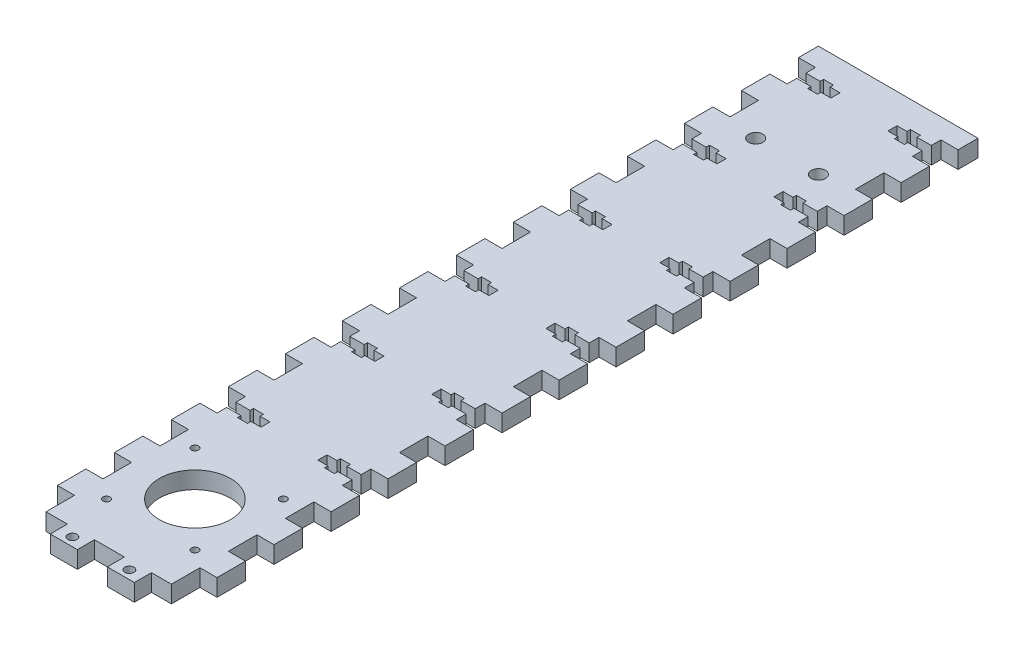
SolidWorks part; units mm, degrees
ref_plane "Plan de face" through (0, 0, 0) normal (0, 0, 1) x (1, 0, 0)
ref_plane "Plan de dessus" through (0, 0, 0) normal (0, 1, 0) x (1, 0, 0)
ref_plane "Plan de droite" through (0, 0, 0) normal (1, 0, 0) x (0, 0, -1)
sketch "Sketch1" plane through (0, 0, 0) normal (0, 0, 1) x (1, 0, 0)
  line L1 (-85.7436, 30.1282) -> (-29.7436, 30.1282)
  line L2 (-85.7436, 30.1282) -> (-85.7436, 24.1282)
  line L3 (-85.7436, 24.1282) -> (-29.7436, 24.1282)
  line L4 (-29.7436, 30.1282) -> (-29.7436, 24.1282)
  dimension "D1" = 56
  dimension "D2" = 6
extrude "Boss-Extrude1" add sketch "Sketch1" along normal blind 277
sketch "Sketch3" plane through (0, 30.1282, 0) normal (0, 1, 0) x (1, 0, 0)
  line L0 (-85.7436, -277) -> (-79.7436, -277)
  line L1 (-29.7436, -277) -> (-85.7436, -277) construction
  line L2 (-29.7436, 0) -> (-85.7436, 0) construction
  line L3 (-57.7436, 0) -> (-57.7436, -277) construction
  line L4 (-29.7436, -277) -> (-35.7436, -277)
  line L5 (-29.7436, -277) -> (-29.7436, -267)
  line L6 (-29.7436, -267) -> (-35.7436, -267)
  line L7 (-35.7436, -277) -> (-35.7436, -267)
  line L8 (-85.7436, -277) -> (-85.7436, -267)
  line L9 (-85.7436, -267) -> (-79.7436, -267)
  line L10 (-79.7436, -277) -> (-79.7436, -267)
  line L11 (-85.7436, -257) -> (-79.7436, -257)
  line L12 (-79.7436, -257) -> (-79.7436, -247)
  line L13 (-85.7436, -247) -> (-79.7436, -247)
  line L14 (-85.7436, -257) -> (-85.7436, -247)
  line L15 (-29.7436, -257) -> (-29.7436, -247)
  line L16 (-29.7436, -257) -> (-35.7436, -257)
  line L17 (-35.7436, -257) -> (-35.7436, -247)
  line L18 (-29.7436, -247) -> (-35.7436, -247)
  line L19 (-85.7436, -237) -> (-79.7436, -237)
  line L20 (-79.7436, -237) -> (-79.7436, -227)
  line L21 (-85.7436, -227) -> (-79.7436, -227)
  line L22 (-85.7436, -237) -> (-85.7436, -227)
  line L23 (-29.7436, -237) -> (-29.7436, -227)
  line L24 (-29.7436, -237) -> (-35.7436, -237)
  line L25 (-35.7436, -237) -> (-35.7436, -227)
  line L26 (-29.7436, -227) -> (-35.7436, -227)
  line L27 (-85.7436, -217) -> (-79.7436, -217)
  line L28 (-79.7436, -217) -> (-79.7436, -207)
  line L29 (-85.7436, -207) -> (-79.7436, -207)
  line L30 (-85.7436, -217) -> (-85.7436, -207)
  line L31 (-29.7436, -217) -> (-29.7436, -207)
  line L32 (-29.7436, -217) -> (-35.7436, -217)
  line L33 (-35.7436, -217) -> (-35.7436, -207)
  line L34 (-29.7436, -207) -> (-35.7436, -207)
  line L35 (-85.7436, -197) -> (-79.7436, -197)
  line L36 (-79.7436, -197) -> (-79.7436, -187)
  line L37 (-85.7436, -187) -> (-79.7436, -187)
  line L38 (-85.7436, -197) -> (-85.7436, -187)
  line L39 (-29.7436, -197) -> (-29.7436, -187)
  line L40 (-29.7436, -197) -> (-35.7436, -197)
  line L41 (-35.7436, -197) -> (-35.7436, -187)
  line L42 (-29.7436, -187) -> (-35.7436, -187)
  line L43 (-85.7436, -177) -> (-79.7436, -177)
  line L44 (-79.7436, -177) -> (-79.7436, -167)
  line L45 (-85.7436, -167) -> (-79.7436, -167)
  line L46 (-85.7436, -177) -> (-85.7436, -167)
  line L47 (-29.7436, -177) -> (-29.7436, -167)
  line L48 (-29.7436, -177) -> (-35.7436, -177)
  line L49 (-35.7436, -177) -> (-35.7436, -167)
  line L50 (-29.7436, -167) -> (-35.7436, -167)
  line L51 (-85.7436, -157) -> (-79.7436, -157)
  line L52 (-79.7436, -157) -> (-79.7436, -147)
  line L53 (-85.7436, -147) -> (-79.7436, -147)
  line L54 (-85.7436, -157) -> (-85.7436, -147)
  line L55 (-29.7436, -157) -> (-29.7436, -147)
  line L56 (-29.7436, -157) -> (-35.7436, -157)
  line L57 (-35.7436, -157) -> (-35.7436, -147)
  line L58 (-29.7436, -147) -> (-35.7436, -147)
  line L59 (-85.7436, -137) -> (-79.7436, -137)
  line L60 (-79.7436, -137) -> (-79.7436, -127)
  line L61 (-85.7436, -127) -> (-79.7436, -127)
  line L62 (-85.7436, -137) -> (-85.7436, -127)
  line L63 (-29.7436, -137) -> (-29.7436, -127)
  line L64 (-29.7436, -137) -> (-35.7436, -137)
  line L65 (-35.7436, -137) -> (-35.7436, -127)
  line L66 (-29.7436, -127) -> (-35.7436, -127)
  line L67 (-85.7436, -117) -> (-79.7436, -117)
  line L68 (-79.7436, -117) -> (-79.7436, -107)
  line L69 (-85.7436, -107) -> (-79.7436, -107)
  line L70 (-85.7436, -117) -> (-85.7436, -107)
  line L71 (-29.7436, -117) -> (-29.7436, -107)
  line L72 (-29.7436, -117) -> (-35.7436, -117)
  line L73 (-35.7436, -117) -> (-35.7436, -107)
  line L74 (-29.7436, -107) -> (-35.7436, -107)
  line L75 (-85.7436, -97) -> (-79.7436, -97)
  line L76 (-79.7436, -97) -> (-79.7436, -87)
  line L77 (-85.7436, -87) -> (-79.7436, -87)
  line L78 (-85.7436, -97) -> (-85.7436, -87)
  line L79 (-29.7436, -97) -> (-29.7436, -87)
  line L80 (-29.7436, -97) -> (-35.7436, -97)
  line L81 (-35.7436, -97) -> (-35.7436, -87)
  line L82 (-29.7436, -87) -> (-35.7436, -87)
  line L83 (-85.7436, -77) -> (-79.7436, -77)
  line L84 (-79.7436, -77) -> (-79.7436, -67)
  line L85 (-85.7436, -67) -> (-79.7436, -67)
  line L86 (-85.7436, -77) -> (-85.7436, -67)
  line L87 (-29.7436, -77) -> (-29.7436, -67)
  line L88 (-29.7436, -77) -> (-35.7436, -77)
  line L89 (-35.7436, -77) -> (-35.7436, -67)
  line L90 (-29.7436, -67) -> (-35.7436, -67)
  line L91 (-85.7436, -57) -> (-79.7436, -57)
  line L92 (-79.7436, -57) -> (-79.7436, -47)
  line L93 (-85.7436, -47) -> (-79.7436, -47)
  line L94 (-85.7436, -57) -> (-85.7436, -47)
  line L95 (-29.7436, -57) -> (-29.7436, -47)
  line L96 (-29.7436, -57) -> (-35.7436, -57)
  line L97 (-35.7436, -57) -> (-35.7436, -47)
  line L98 (-29.7436, -47) -> (-35.7436, -47)
  line L99 (-85.7436, -37) -> (-79.7436, -37)
  line L100 (-79.7436, -37) -> (-79.7436, -27)
  line L101 (-85.7436, -27) -> (-79.7436, -27)
  line L102 (-85.7436, -37) -> (-85.7436, -27)
  line L103 (-29.7436, -37) -> (-29.7436, -27)
  line L104 (-29.7436, -37) -> (-35.7436, -37)
  line L105 (-35.7436, -37) -> (-35.7436, -27)
  line L106 (-29.7436, -27) -> (-35.7436, -27)
  line L107 (-85.7436, -17) -> (-79.7436, -17)
  line L108 (-79.7436, -17) -> (-79.7436, -7)
  line L109 (-85.7436, -7) -> (-79.7436, -7)
  line L110 (-85.7436, -17) -> (-85.7436, -7)
  line L111 (-29.7436, -17) -> (-29.7436, -7)
  line L112 (-29.7436, -17) -> (-35.7436, -17)
  line L113 (-35.7436, -17) -> (-35.7436, -7)
  line L114 (-29.7436, -7) -> (-35.7436, -7)
  dimension "D1" = 6
  dimension "D2" = 10
  dimension "D3" = 14
extrude "Cut-Extrude1" cut sketch "Sketch3" against normal through all
sketch "Sketch6" plane through (0, 0, 277) normal (0, 0, 1) x (1, 0, 0)
  line L0 (-35.7436, 30.1282) -> (-79.7436, 30.1282) construction
  line L1 (-72.2436, 30.1282) -> (-62.7436, 30.1282)
  line L2 (-72.2436, 30.1282) -> (-72.2436, 24.1282)
  line L3 (-72.2436, 24.1282) -> (-62.7436, 24.1282)
  line L4 (-62.7436, 30.1282) -> (-62.7436, 24.1282)
  line L5 (-79.7436, 24.1282) -> (-35.7436, 24.1282) construction
  line L6 (-79.7436, 24.1282) -> (-79.7436, 30.1282) construction
  line L7 (-52.2436, 30.1282) -> (-52.2436, 24.1282)
  line L8 (-52.2436, 30.1282) -> (-42.7436, 30.1282)
  line L9 (-42.7436, 30.1282) -> (-42.7436, 24.1282)
  line L10 (-52.2436, 24.1282) -> (-42.7436, 24.1282)
  dimension "D1" = 7.5
  dimension "D2" = 9.5
  dimension "D3" = 2
extrude "Boss-Extrude2" add sketch "Sketch6" along normal blind 6
sketch "Sketch9" plane through (-35.7436, 0, 0) normal (1, 0, 0) x (0, 0, -1)
  line L0 (-257, 24.1282) -> (-247, 30.1282) construction
  line L1 (-247, 24.1282) -> (-257, 24.1282) construction
  line L2 (-250.4, 30.1282) -> (-253.6, 30.1282)
  line L3 (-250.4, 30.1282) -> (-250.4, 24.1282)
  line L4 (-250.4, 24.1282) -> (-253.6, 24.1282)
  line L5 (-253.6, 30.1282) -> (-253.6, 24.1282)
  line L6 (-250.4, 30.1282) -> (-253.6, 24.1282) construction
  line L7 (-250.4, 24.1282) -> (-253.6, 30.1282) construction
  line L8 (-210.4, 30.1282) -> (-210.4, 24.1282)
  line L9 (-210.4, 30.1282) -> (-213.6, 30.1282)
  line L10 (-213.6, 30.1282) -> (-213.6, 24.1282)
  line L11 (-210.4, 24.1282) -> (-213.6, 24.1282)
  line L12 (-170.4, 30.1282) -> (-170.4, 24.1282)
  line L13 (-170.4, 30.1282) -> (-173.6, 30.1282)
  line L14 (-173.6, 30.1282) -> (-173.6, 24.1282)
  line L15 (-170.4, 24.1282) -> (-173.6, 24.1282)
  line L16 (-130.4, 30.1282) -> (-130.4, 24.1282)
  line L17 (-130.4, 30.1282) -> (-133.6, 30.1282)
  line L18 (-133.6, 30.1282) -> (-133.6, 24.1282)
  line L19 (-130.4, 24.1282) -> (-133.6, 24.1282)
  line L20 (-90.4, 30.1282) -> (-90.4, 24.1282)
  line L21 (-90.4, 30.1282) -> (-93.6, 30.1282)
  line L22 (-93.6, 30.1282) -> (-93.6, 24.1282)
  line L23 (-90.4, 24.1282) -> (-93.6, 24.1282)
  line L24 (-50.4, 30.1282) -> (-50.4, 24.1282)
  line L25 (-50.4, 30.1282) -> (-53.6, 30.1282)
  line L26 (-53.6, 30.1282) -> (-53.6, 24.1282)
  line L27 (-50.4, 24.1282) -> (-53.6, 24.1282)
  line L28 (-10.4, 30.1282) -> (-10.4, 24.1282)
  line L29 (-10.4, 30.1282) -> (-13.6, 30.1282)
  line L30 (-13.6, 30.1282) -> (-13.6, 24.1282)
  line L31 (-10.4, 24.1282) -> (-13.6, 24.1282)
  point P4 (-252, 27.1282)
  dimension "D1" = 3.2
  dimension "D2" = 7
extrude "Cut-Extrude2" cut sketch "Sketch9" against normal blind 12
sketch "Sketch10" plane through (-79.7436, 0, 0) normal (-1, 0, 0) x (0, 0, 1)
  line L0 (257, 30.1282) -> (247, 24.1282) construction
  line L1 (257, 30.1282) -> (247, 30.1282) construction
  line L2 (250.4, 24.1282) -> (253.6, 24.1282)
  line L3 (250.4, 24.1282) -> (250.4, 30.1282)
  line L4 (250.4, 30.1282) -> (253.6, 30.1282)
  line L5 (253.6, 24.1282) -> (253.6, 30.1282)
  line L6 (250.4, 24.1282) -> (253.6, 30.1282) construction
  line L7 (250.4, 30.1282) -> (253.6, 24.1282) construction
  line L8 (210.4, 24.1282) -> (210.4, 30.1282)
  line L9 (210.4, 24.1282) -> (213.6, 24.1282)
  line L10 (213.6, 24.1282) -> (213.6, 30.1282)
  line L11 (210.4, 30.1282) -> (213.6, 30.1282)
  line L12 (170.4, 24.1282) -> (170.4, 30.1282)
  line L13 (170.4, 24.1282) -> (173.6, 24.1282)
  line L14 (173.6, 24.1282) -> (173.6, 30.1282)
  line L15 (170.4, 30.1282) -> (173.6, 30.1282)
  line L16 (130.4, 24.1282) -> (130.4, 30.1282)
  line L17 (130.4, 24.1282) -> (133.6, 24.1282)
  line L18 (133.6, 24.1282) -> (133.6, 30.1282)
  line L19 (130.4, 30.1282) -> (133.6, 30.1282)
  line L20 (90.4, 24.1282) -> (90.4, 30.1282)
  line L21 (90.4, 24.1282) -> (93.6, 24.1282)
  line L22 (93.6, 24.1282) -> (93.6, 30.1282)
  line L23 (90.4, 30.1282) -> (93.6, 30.1282)
  line L24 (50.4, 24.1282) -> (50.4, 30.1282)
  line L25 (50.4, 24.1282) -> (53.6, 24.1282)
  line L26 (53.6, 24.1282) -> (53.6, 30.1282)
  line L27 (50.4, 30.1282) -> (53.6, 30.1282)
  line L28 (10.4, 24.1282) -> (10.4, 30.1282)
  line L29 (10.4, 24.1282) -> (13.6, 24.1282)
  line L30 (13.6, 24.1282) -> (13.6, 30.1282)
  line L31 (10.4, 30.1282) -> (13.6, 30.1282)
  point P4 (252, 27.1282)
  dimension "D1" = 3.2
  dimension "D2" = 7
extrude "Cut-Extrude3" cut sketch "Sketch10" against normal blind 12
sketch "Sketch11" plane through (0, 24.1282, 0) normal (0, -1, 0) x (1, 0, 0)
  line L0 (-57.7436, 277) -> (-57.7436, 0) construction
  line L1 (-74.7436, 254.8) -> (-71.2436, 254.8)
  line L2 (-74.7436, 254.8) -> (-74.7436, 249.2)
  line L3 (-74.7436, 249.2) -> (-71.2436, 249.2)
  line L4 (-71.2436, 254.8) -> (-71.2436, 249.2)
  line L6 (-85.7436, 0) -> (-29.7436, 0) construction
  line L7 (-47.7436, 250.4) -> (-47.7436, 253.6) construction
  line L8 (-79.7436, 257) -> (-79.7436, 253.6) construction
  line L9 (-40.7436, 249.2) -> (-44.2436, 249.2)
  line L10 (-44.2436, 254.8) -> (-44.2436, 249.2)
  line L11 (-40.7436, 254.8) -> (-44.2436, 254.8)
  line L12 (-40.7436, 254.8) -> (-40.7436, 249.2)
  line L13 (-74.7436, 214.8) -> (-74.7436, 209.2)
  line L14 (-74.7436, 214.8) -> (-71.2436, 214.8)
  line L15 (-71.2436, 214.8) -> (-71.2436, 209.2)
  line L16 (-74.7436, 209.2) -> (-71.2436, 209.2)
  line L17 (-40.7436, 209.2) -> (-44.2436, 209.2)
  line L18 (-44.2436, 214.8) -> (-44.2436, 209.2)
  line L19 (-40.7436, 214.8) -> (-44.2436, 214.8)
  line L20 (-40.7436, 214.8) -> (-40.7436, 209.2)
  line L21 (-74.7436, 174.8) -> (-74.7436, 169.2)
  line L22 (-74.7436, 174.8) -> (-71.2436, 174.8)
  line L23 (-71.2436, 174.8) -> (-71.2436, 169.2)
  line L24 (-74.7436, 169.2) -> (-71.2436, 169.2)
  line L25 (-40.7436, 169.2) -> (-44.2436, 169.2)
  line L26 (-44.2436, 174.8) -> (-44.2436, 169.2)
  line L27 (-40.7436, 174.8) -> (-44.2436, 174.8)
  line L28 (-40.7436, 174.8) -> (-40.7436, 169.2)
  line L29 (-74.7436, 134.8) -> (-74.7436, 129.2)
  line L30 (-74.7436, 134.8) -> (-71.2436, 134.8)
  line L31 (-71.2436, 134.8) -> (-71.2436, 129.2)
  line L32 (-74.7436, 129.2) -> (-71.2436, 129.2)
  line L33 (-40.7436, 129.2) -> (-44.2436, 129.2)
  line L34 (-44.2436, 134.8) -> (-44.2436, 129.2)
  line L35 (-40.7436, 134.8) -> (-44.2436, 134.8)
  line L36 (-40.7436, 134.8) -> (-40.7436, 129.2)
  line L37 (-74.7436, 94.8) -> (-74.7436, 89.2)
  line L38 (-74.7436, 94.8) -> (-71.2436, 94.8)
  line L39 (-71.2436, 94.8) -> (-71.2436, 89.2)
  line L40 (-74.7436, 89.2) -> (-71.2436, 89.2)
  line L41 (-40.7436, 89.2) -> (-44.2436, 89.2)
  line L42 (-44.2436, 94.8) -> (-44.2436, 89.2)
  line L43 (-40.7436, 94.8) -> (-44.2436, 94.8)
  line L44 (-40.7436, 94.8) -> (-40.7436, 89.2)
  line L45 (-74.7436, 54.8) -> (-74.7436, 49.2)
  line L46 (-74.7436, 54.8) -> (-71.2436, 54.8)
  line L47 (-71.2436, 54.8) -> (-71.2436, 49.2)
  line L48 (-74.7436, 49.2) -> (-71.2436, 49.2)
  line L49 (-40.7436, 49.2) -> (-44.2436, 49.2)
  line L50 (-44.2436, 54.8) -> (-44.2436, 49.2)
  line L51 (-40.7436, 54.8) -> (-44.2436, 54.8)
  line L52 (-40.7436, 54.8) -> (-40.7436, 49.2)
  line L53 (-74.7436, 14.8) -> (-74.7436, 9.2)
  line L55 (-74.7436, 14.8) -> (-71.2436, 14.8)
  line L56 (-71.2436, 14.8) -> (-71.2436, 9.2)
  line L57 (-74.7436, 9.2) -> (-71.2436, 9.2)
  line L58 (-40.7436, 9.2) -> (-44.2436, 9.2)
  line L59 (-44.2436, 14.8) -> (-44.2436, 9.2)
  line L60 (-40.7436, 14.8) -> (-44.2436, 14.8)
  line L61 (-40.7436, 14.8) -> (-40.7436, 9.2)
  point P10 (-74.7436, 252)
  point P52 (-47.7436, 252)
  dimension "D1" = 5.6
  dimension "D3" = 5
  dimension "D4" = 3.5
  dimension "D5" = 7
extrude "Cut-Extrude4" cut sketch "Sketch11" against normal blind 12
sketch "Sketch12" plane through (0, 24.1282, 0) normal (0, -1, 0) x (1, 0, 0)
  line L2 (-52.2436, 283) -> (-52.2436, 277) construction
  line L3 (-42.7436, 283) -> (-52.2436, 283) construction
  line L4 (-62.7436, 283) -> (-72.2436, 283) construction
  circle A0 centre (-67.4936, 280) radius 1.6
  circle A1 centre (-47.4936, 280) radius 1.6
  point P2 (-52.2436, 280)
  point P5 (-47.4936, 283)
  point P12 (-67.4936, 283)
  dimension "D1" = 3.2
  dimension "D2" = 3.2
extrude "Cut-Extrude5" cut sketch "Sketch12" against normal blind 12
sketch "Sketch17" plane through (0, 30.1282, 0) normal (0, 1, 0) x (1, 0, 0)
  line L1 (-35.7436, -257) -> (-79.7436, -257)
  line L2 (-35.7436, -257) -> (-35.7436, -247)
  line L3 (-35.7436, -247) -> (-79.7436, -247)
  line L4 (-79.7436, -257) -> (-79.7436, -247)
extrude "Boss-Extrude5" add sketch "Sketch17" against normal through all
sketch "Sketch14" plane through (0, 24.1282, 0) normal (0, -1, 0) x (1, 0, 0)
  line L0 (-72.9936, 262.5) -> (-41.9936, 262.5) construction
  line L1 (-72.9936, 262.5) -> (-72.9936, 231.5) construction
  line L2 (-72.9936, 231.5) -> (-41.9936, 231.5) construction
  line L3 (-41.9936, 262.5) -> (-41.9936, 231.5) construction
  line L4 (-52.2436, 277) -> (-62.7436, 277) construction
  line L5 (-42.7436, 277) -> (-35.7436, 277) construction
  circle A0 centre (-72.9936, 262.5) radius 1.25
  circle A1 centre (-41.9936, 262.5) radius 1.25
  circle A2 centre (-41.9936, 231.5) radius 1.25
  circle A3 centre (-72.9936, 231.5) radius 1.25
  circle A4 centre (-57.4936, 247) radius 12.5
  point P12 (-57.4936, 277)
  point P15 (-57.4936, 262.5)
  point P17 (-72.9936, 247)
  dimension "D5" = 25
  dimension "D1" = 31
  dimension "D2" = 31
  dimension "D3" = 30
extrude "Cut-Extrude6" cut sketch "Sketch14" against normal through all both and the other way through all
sketch "Sketch15" plane through (0, 24.1282, 0) normal (0, -1, 0) x (1, 0, 0)
  line L0 (-57.7436, 0) -> (-57.7436, 66.6112) construction
  line L1 (-85.7436, 0) -> (-29.7436, 0) construction
  circle A0 centre (-68.7436, 39) radius 2.5
  circle A1 centre (-46.7436, 39) radius 2.5
  point P9 (-57.7436, 0)
  dimension "D1" = 5
  dimension "D2" = 11
  dimension "D3" = 39
extrude "Cut-Extrude7" cut sketch "Sketch15" against normal through all
